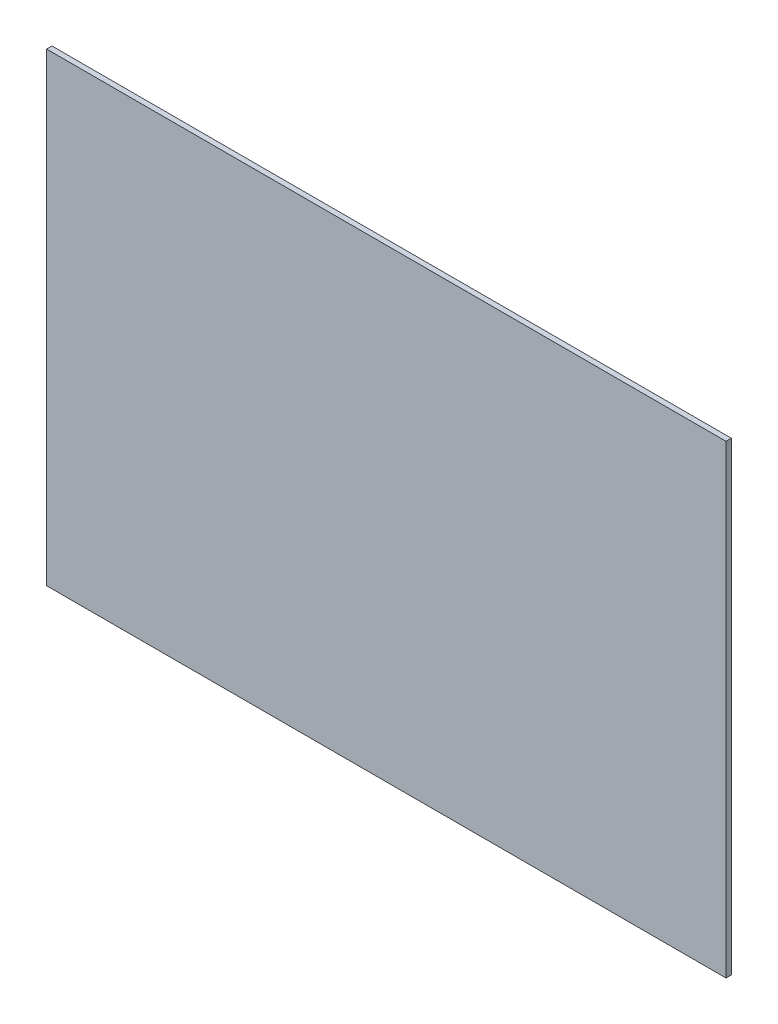
SolidWorks part; units mm, degrees
ref_plane "Plan de face" through (0, 0, 0) normal (0, 0, 1) x (1, 0, 0)
ref_plane "Plan de dessus" through (0, 0, 0) normal (0, 1, 0) x (1, 0, 0)
ref_plane "Plan de droite" through (0, 0, 0) normal (1, 0, 0) x (0, 0, -1)
sketch "Esquisse1" plane through (0, 0, 0) normal (0, 0, 1) x (1, 0, 0)
  line L1 (0, 0) -> (381.9, 0)
  line L2 (0, 0) -> (0, 261.3)
  line L3 (0, 261.3) -> (381.9, 261.3)
  line L4 (381.9, 0) -> (381.9, 261.3)
  dimension "D1" = 381.9
  dimension "D2" = 261.3
extrude "Boss.-Extru.1" add sketch "Esquisse1" along normal blind 3
